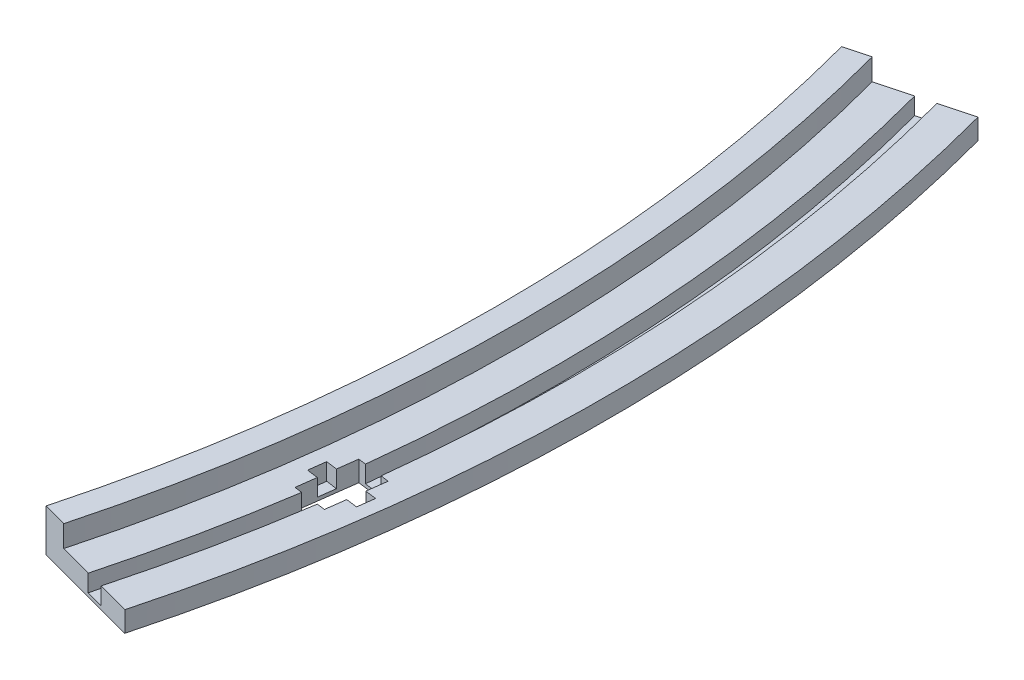
SolidWorks part; units mm, degrees
ref_plane "Ebene vorne" through (0, 0, 0) normal (0, 0, 1) x (1, 0, 0)
ref_plane "Ebene oben" through (0, 0, 0) normal (0, 1, 0) x (1, 0, 0)
ref_plane "Ebene rechts" through (0, 0, 0) normal (1, 0, 0) x (0, 0, -1)
sketch "Skizze1" plane through (0, 0, 0) normal (0, 1, 0) x (1, 0, 0)
  line L0 (0, 0) -> (290, 0) construction
  line L1 (280.1185, 75.0575) -> (261.1863, 69.9847)
  line L2 (261.1863, -69.9847) -> (280.1185, -75.0575)
  line L3 (0, 0) -> (280.1185, 75.0575) construction
  line L4 (0, 0) -> (280.1185, -75.0575) construction
  arc A0 (261.1863, -69.9847) -> (261.1863, 69.9847) centre (0, 0) ccw
  arc A1 (280.1185, -75.0575) -> (280.1185, 75.0575) centre (0, 0) ccw
  dimension "D1" = 290
  dimension "D2" = 270.4
  dimension "D5" = 15
  dimension "D6" = 15
extrude "Aufsatz-Linear austragen1" add sketch "Skizze1" along normal blind 3.6
sketch "Skizze2" plane through (0, 3.6, 0) normal (0, 1, 0) x (1, 0, 0)
  line L0 (261.1863, -69.9847) -> (280.1185, -75.0575) construction
  line L1 (280.1185, 75.0575) -> (261.1863, 69.9847) construction
  line L3 (271.3286, 72.7023) -> (274.4195, 73.5305)
  line L4 (271.3286, -72.7023) -> (274.4195, -73.5305)
  arc A2 (271.3286, -72.7023) -> (271.3286, 72.7023) centre (0, 0) ccw
  arc A3 (274.4195, -73.5305) -> (274.4195, 73.5305) centre (0, 0) ccw
  dimension "D1" = 5.9
  dimension "D2" = 3.2
extrude "Schnitt-Linear austragen1" cut sketch "Skizze2" against normal blind 3
sketch "Skizze3" plane through (0, 3.6, 0) normal (0, 1, 0) x (1, 0, 0)
  line L0 (261.1863, -69.9847) -> (271.3286, -72.7023) construction
  line L1 (271.3286, 72.7023) -> (261.1863, 69.9847) construction
  line L3 (0, 0) -> (290, 0) construction
  line L4 (0, 0) -> (280.0832, -36.8736) construction
  line L10 (276.4562, -41.4393) -> (282.4049, -42.2225)
  line L11 (282.4049, -42.2225) -> (283.7101, -32.308)
  line L12 (283.7101, -32.308) -> (277.7615, -31.5248)
  line L13 (277.7615, -31.5248) -> (276.4562, -41.4393)
  line L14 (276.4562, -41.4393) -> (283.7101, -32.308) construction
  arc A0 (152.1333, -40.764) -> (152.1333, 40.764) centre (0, 0) ccw construction
  arc A1 (272.874, -73.1164) -> (272.874, 73.1164) centre (0, 0) ccw construction
  arc A2 (280.1185, -75.0575) -> (280.1185, 75.0575) centre (0, 0) ccw construction
  point P23 (280.0832, -36.8736)
  dimension "D1" = 157.5
  dimension "D2" = 282.5
  dimension "D3" = 10
  dimension "D4" = 6
  dimension "7.5" = 7.5
extrude "Schnitt-Linear austragen2" cut sketch "Skizze3" against normal through all
sketch "Skizze4" plane through (0, 3.6, 0) normal (0, 1, 0) x (1, 0, 0)
  line L4 (275.3217, -34.7339) -> (285.2362, -36.0391)
  line L5 (285.2362, -36.0391) -> (284.8446, -39.0134)
  line L6 (284.8446, -39.0134) -> (274.9302, -37.7082)
  line L7 (274.9302, -37.7082) -> (275.3217, -34.7339)
  line L10 (277.7615, -31.5248) -> (276.4562, -41.4393) construction
  line L11 (282.2785, -32.1195) -> (279.1054, -31.7018) construction
  line L14 (276.4562, -41.4393) -> (283.7101, -32.308) construction
  line L15 (276.4562, -41.4393) -> (277.8001, -41.6162) construction
  line L16 (275.3217, -34.7339) -> (284.8446, -39.0134) construction
  point P27 (280.0832, -36.8736)
  point P28 (280.0832, -36.8736)
  dimension "D1" = 10
  dimension "D2" = 3
extrude "Schnitt-Linear austragen3" cut sketch "Skizze4" against normal blind 3
sketch "Skizze5" plane through (0, 3.6, 0) normal (0, 1, 0) x (1, 0, 0)
  line L0 (261.1863, 69.9847) -> (265.4364, 71.1235)
  line L1 (265.4364, -71.1235) -> (261.1863, -69.9847)
  line L2 (261.1863, -69.9847) -> (271.3286, -72.7023) construction
  line L3 (271.3286, 72.7023) -> (261.1863, 69.9847) construction
  arc A0 (261.1863, -69.9847) -> (261.1863, 69.9847) centre (0, 0) ccw
  arc A1 (265.4364, -71.1235) -> (265.4364, 71.1235) centre (0, 0) ccw
  dimension "D1" = 4.4
extrude "Aufsatz-Linear austragen2" add sketch "Skizze5" along normal blind 3.8
equation "\"D6@Skizze1\"=\"D5@Skizze1\""
